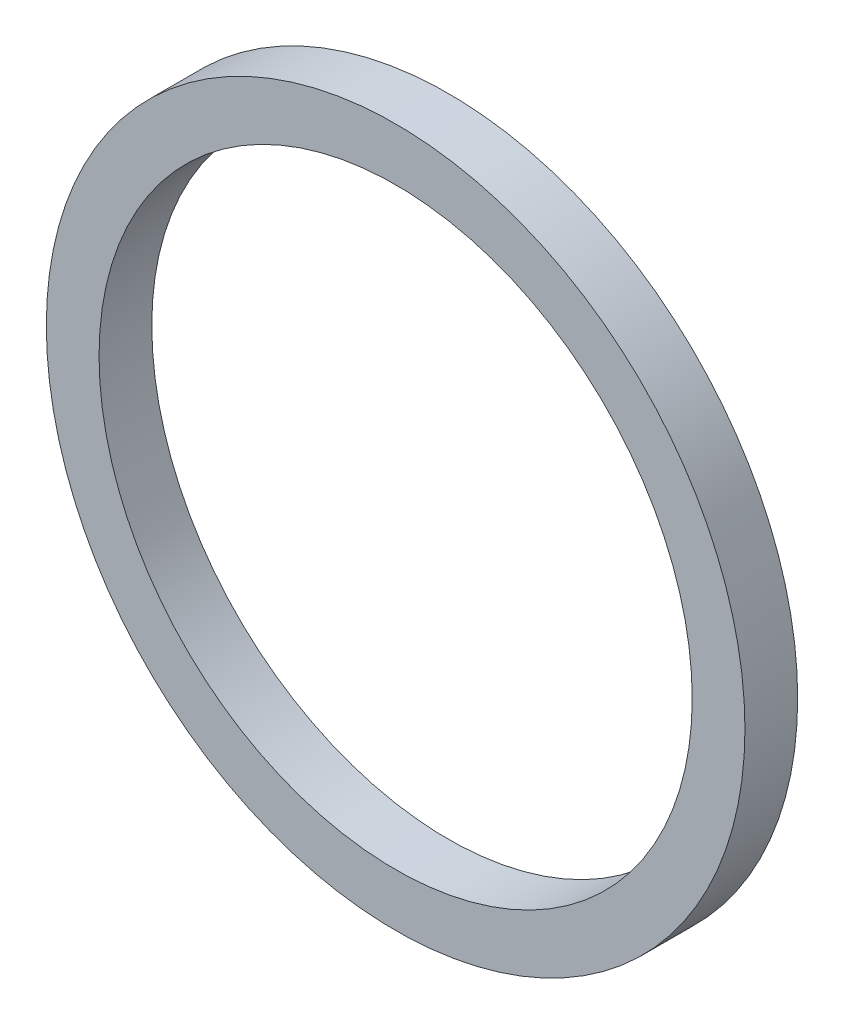
SolidWorks part; units mm, degrees
material "氧化铝"
ref_plane "前视基准面" through (0, 0, 0) normal (0, 0, 1) x (1, 0, 0)
ref_plane "上视基准面" through (0, 0, 0) normal (0, 1, 0) x (1, 0, 0)
ref_plane "右视基准面" through (0, 0, 0) normal (1, 0, 0) x (0, 0, -1)
other "Configuration Table"
sketch "草图1" plane through (0, 0, 0) normal (0, 0, 1) x (1, 0, 0)
  circle A0 centre (0, 0) radius 45
  circle A1 centre (0, 0) radius 53
  dimension "D1" = 90
  dimension "D2" = 106
extrude "凸台-拉伸1" add sketch "草图1" along normal mid plane 8 contours A1 | A0
